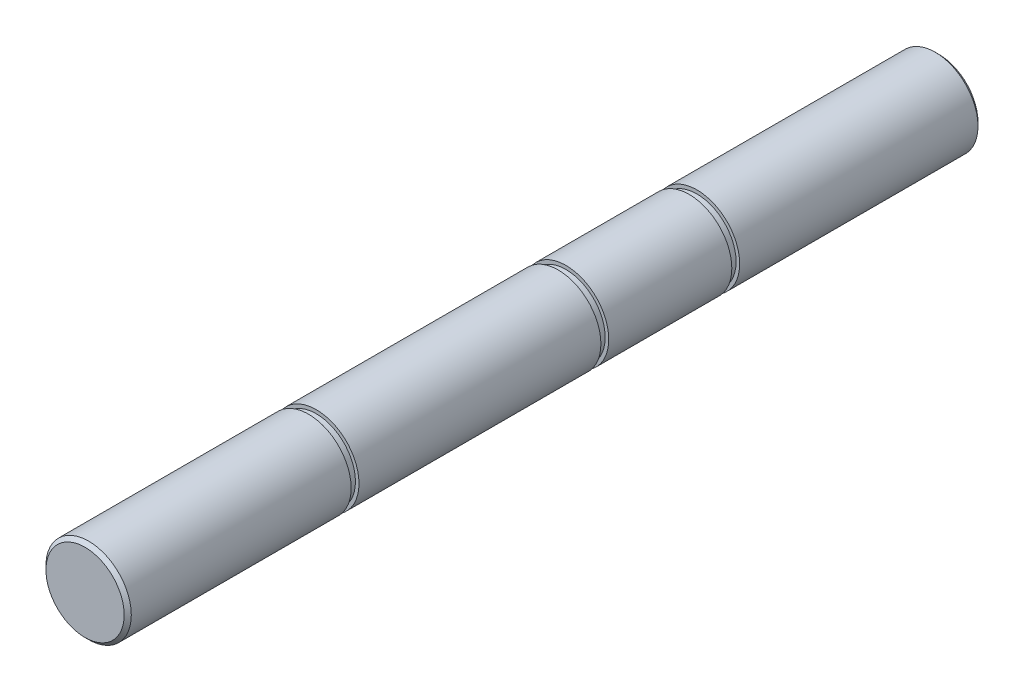
SolidWorks part; units mm, degrees
material "AISI 304"
ref_plane "前视基准面" through (0, 0, 0) normal (0, 0, 1) x (1, 0, 0)
ref_plane "上视基准面" through (0, 0, 0) normal (0, 1, 0) x (1, 0, 0)
ref_plane "右视基准面" through (0, 0, 0) normal (1, 0, 0) x (0, 0, -1)
sketch "草图1" plane through (0, 0, 0) normal (0, 0, 1) x (1, 0, 0)
  circle A0 centre (0, 0) radius 6
  dimension "D1" = 12
extrude "凸台-拉伸1" add sketch "草图1" along normal blind 120
sketch "草图2" plane through (0, 0, 0) normal (0, 1, 0) x (1, 0, 0)
  line L0 (0, 10.1337) -> (0, -29.0927) construction
  line L1 (0, -58) -> (0, -84) construction
  line L2 (2, -58) -> (2, -84)
  line L3 (-2, -58) -> (-2, -84)
  line L4 (-6, -120) -> (6, -120) construction
  arc A0 (2, -58) -> (-2, -58) centre (0, -58) ccw
  arc A1 (-2, -84) -> (2, -84) centre (0, -84) ccw
  point P5 (0, -71)
  dimension "D3" = 36
  dimension "D1" = 4
  dimension "D2" = 26
extrude "切除-拉伸1" cut sketch "草图2" against normal blind 10 from offset 3.5 offset against normal yes
sketch "草图3" plane through (0, 0, 0) normal (1, 0, 0) x (0, 0, -1)
  line L0 (-87.5, 9.9164) -> (-87.5, -8.9175) construction
  line L1 (-120, 6) -> (-120, -6) construction
  line L2 (-87.5, 6) -> (-88.6, 6)
  line L3 (0, 6) -> (-120, 6) construction
  line L4 (-88.6, 6) -> (-88.6, 5.5)
  line L5 (-88.6, 5.5) -> (-87.5, 5.5)
  line L6 (-87.5, 5.5) -> (-87.5, 6)
  line L7 (-130.6611, 0) -> (23.7079, 0) construction
  line L9 (-35.1, 6) -> (-34, 6)
  line L10 (-35.1, 6) -> (-35.1, 5.5)
  line L11 (-35.1, 5.5) -> (-34, 5.5)
  line L12 (-34, 6) -> (-34, 5.5)
  line L13 (-53.5, 6) -> (-52.4, 6)
  line L14 (-53.5, 6) -> (-53.5, 5.5)
  line L15 (-53.5, 5.5) -> (-52.4, 5.5)
  line L16 (-52.4, 6) -> (-52.4, 5.5)
  dimension "D1" = 32.5
  dimension "D2" = 1.1
  dimension "D3" = 0.5
  dimension "D4" = 0.5
  dimension "D5" = 1.1
  dimension "D6" = 17.3
  dimension "D7" = 1.1
  dimension "D8" = 0.5
  dimension "D9" = 34
revolve "切除-旋转1" cut sketch "草图3" angle 360 about L7
chamfer "倒角1" distance 0.5 angle 45 2 edges at (6, 0, 0) (6, 0, 120)
